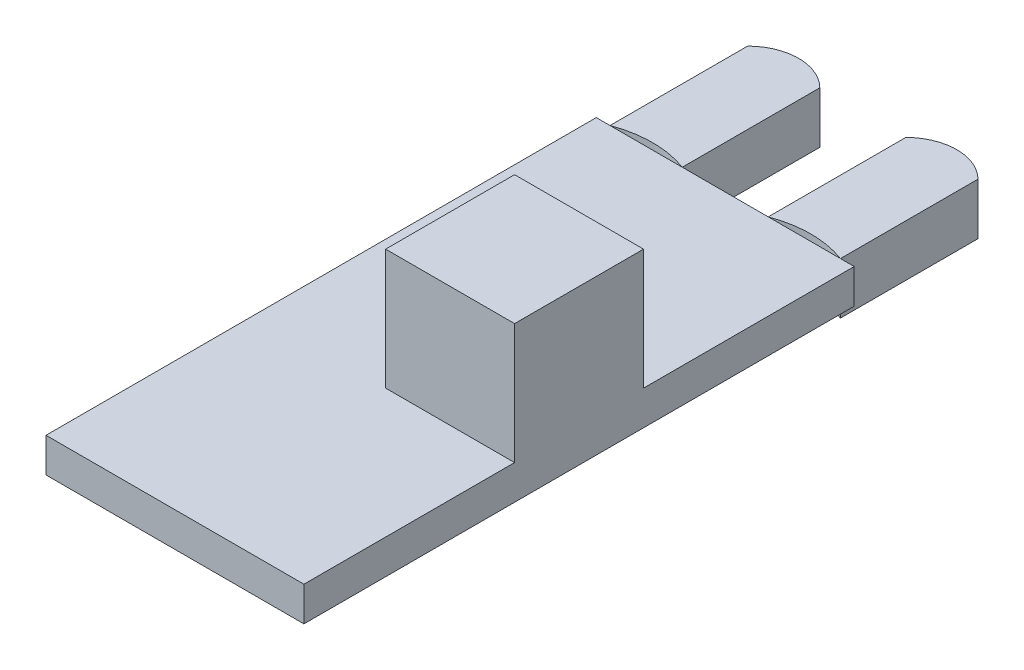
SolidWorks part; units mm, degrees
ref_plane "Front Plane" through (0, 0, 0) normal (0, 0, 1) x (1, 0, 0)
ref_plane "Top Plane" through (0, 0, 0) normal (0, 1, 0) x (1, 0, 0)
ref_plane "Right Plane" through (0, 0, 0) normal (1, 0, 0) x (0, 0, -1)
sketch "Sketch1" plane through (0, 0, 0) normal (0, 1, 0) x (1, 0, 0)
  line L1 (-7.5, 16) -> (7.5, 16)
  line L2 (-7.5, 16) -> (-7.5, -16)
  line L3 (-7.5, -16) -> (7.5, -16)
  line L4 (7.5, 16) -> (7.5, -16)
  line L5 (-7.5, 16) -> (7.5, -16) construction
  line L6 (-7.5, -16) -> (7.5, 16) construction
  point P0 (0, 0)
  dimension "D1" = 15
  dimension "D2" = 32
extrude "Boss-Extrude1" add sketch "Sketch1" along normal blind 2
sketch "Sketch2" plane through (0, 2, 0) normal (0, 1, 0) x (1, 0, 0)
  line L0 (7.5, -16) -> (7.5, 16) construction
  line L1 (0, 3.75) -> (7.5, 3.75)
  line L2 (0, 3.75) -> (0, -3.75)
  line L3 (0, -3.75) -> (7.5, -3.75)
  line L4 (7.5, 3.75) -> (7.5, -3.75)
  line L5 (0, 3.75) -> (7.5, -3.75) construction
  line L6 (0, -3.75) -> (7.5, 3.75) construction
  point P0 (3.75, 0)
  point P7 (0, 0)
  dimension "D1" = 7.5
  dimension "D2" = 7.5
extrude "Boss-Extrude2" add sketch "Sketch2" along normal blind 7
ref_plane "Plane1" through (0, 2, 0) normal (0, 1, 0) x (1, 0, 0)
sketch "Sketch6" plane through (0, 2, 0) normal (0, 1, 0) x (1, 0, 0)
  line L0 (7.5, 16) -> (-7.5, 16) construction
  line L1 (0, 0) -> (0, 36.1933) construction
  line L2 (-6.7, 16) -> (-6.7, 24)
  line L3 (-2.5, 24) -> (-2.5, 16)
  line L4 (2.5, 16) -> (2.5, 24)
  line L5 (6.7, 24) -> (6.7, 16)
  arc A0 (6.7, 16) -> (2.5, 16) centre (4.6, 10.3795) ccw
  arc A1 (-6.7, 16) -> (-2.5, 16) centre (-4.6, 10.3795) cw
  arc A2 (-6.7, 24) -> (-2.5, 24) centre (-4.6, 21.9) cw
  arc A3 (2.5, 24) -> (6.7, 24) centre (4.6, 21.9) cw
  point P20 (0, 0)
  point P21 (0, 0)
  point P22 (0, 0)
  point P23 (0, 0)
  dimension "D1" = 6
  dimension "D2" = 6
  dimension "D8" = 2.9698
  dimension "D9" = 2.9698
  dimension "D3" = 0.8
  dimension "D4" = 0.8
  dimension "D5" = 2.5
  dimension "D6" = 2.5
  dimension "D7" = 8
extrude "Boss-Extrude3" add sketch "Sketch6" against normal blind 3 separate body
